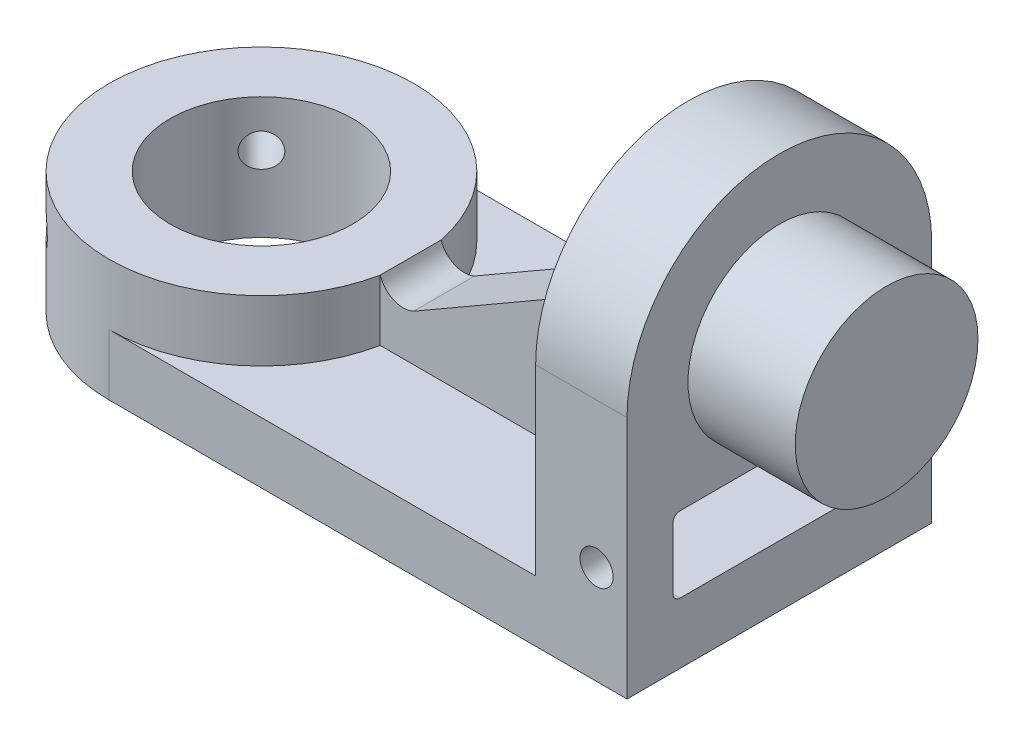
SolidWorks part; units mm, degrees
material "Alloy Steel"
ref_plane "Front Plane" through (0, 0, 0) normal (0, 0, 1) x (1, 0, 0)
ref_plane "Top Plane" through (0, 0, 0) normal (0, 1, 0) x (1, 0, 0)
ref_plane "Right Plane" through (0, 0, 0) normal (1, 0, 0) x (0, 0, -1)
sketch "Sketch4" plane through (0, 0, 0) normal (0, 1, 0) x (1, 0, 0)
  line L1 (-15.9224, 13.1738) -> (38.0526, 13.1738)
  line L2 (-15.9224, 13.1738) -> (-15.9224, -18.5762)
  line L3 (-15.9224, -18.5762) -> (38.0526, -18.5762)
  line L4 (38.0526, 13.1738) -> (38.0526, -18.5762)
  arc A0 (-15.9224, 13.1738) -> (-15.9224, -18.5762) centre (-15.9224, -2.7012) ccw
  dimension "D1" = 53.975
  dimension "D2" = 31.75
extrude "Boss-Extrude1" add sketch "Sketch4" along normal blind 6.35 contours L2 A0 | L4 L1 L2 L3
sketch "Sketch5" plane through (0, 6.35, 0) normal (0, 1, 0) x (1, 0, 0)
  circle A0 centre (-15.9224, -2.7012) radius 15.875
  arc A1 (-15.9224, 13.1738) -> (-15.9224, -18.5762) centre (-15.9224, -2.7012) ccw construction
  dimension "D1" = 31.75
extrude "Boss-Extrude2" add sketch "Sketch5" along normal blind 6.35
sketch "Sketch6" plane through (0, 12.7, 0) normal (0, 1, 0) x (1, 0, 0)
  circle A0 centre (-15.9224, -2.7012) radius 9.525
  circle A1 centre (-15.9224, -2.7012) radius 15.875 construction
  dimension "D1" = 19.05
extrude "Cut-Extrude1" cut sketch "Sketch6" against normal through all both and the other way through all
sketch "Sketch7" plane through (0, 0, 18.5762) normal (0, 0, 1) x (1, 0, 0)
  line L0 (-0.0474, 12.7) -> (-31.7974, 12.7) construction
  line L1 (38.0526, 0) -> (28.5276, 0)
  line L2 (38.0526, 0) -> (38.0526, 25.4)
  line L3 (38.0526, 25.4) -> (28.5276, 25.4)
  line L4 (28.5276, 0) -> (28.5276, 25.4)
  dimension "D1" = 9.525
  dimension "D2" = 12.7
extrude "Boss-Extrude3" add sketch "Sketch7" against normal up to surface (31.75 mm away) up to face at (11.0651, 3.175, -13.1738)
sketch "Sketch8" plane through (38.0526, 0, 0) normal (1, 0, 0) x (0, 0, -1)
  line L0 (13.1738, 25.4) -> (-18.5762, 25.4) construction
  line L1 (-18.5762, 25.4) -> (13.1738, 25.4)
  arc A0 (-18.5762, 25.4) -> (13.1738, 25.4) centre (-2.7012, 25.4) cw
extrude "Boss-Extrude4" add sketch "Sketch8" against normal up to surface (9.525 mm away) up to face at (28.5276, 15.875, 2.7012)
sketch "Sketch9" plane through (38.0526, 0, 0) normal (1, 0, 0) x (0, 0, -1)
  circle A0 centre (-2.7012, 25.4) radius 9.525
  arc A1 (13.1738, 25.4) -> (-18.5762, 25.4) centre (-2.7012, 25.4) ccw construction
  dimension "D1" = 19.05
extrude "Boss-Extrude5" add sketch "Sketch9" along normal blind 11.176
sketch "Sketch10" plane through (38.0526, 0, 0) normal (1, 0, 0) x (0, 0, -1)
  line L0 (-18.5762, 25.4) -> (-18.5762, 0) construction
  line L1 (-13.039, 14.224) -> (7.662, 14.224)
  line L2 (-13.801, 13.462) -> (-13.801, 7.112)
  line L3 (-13.039, 6.35) -> (7.662, 6.35)
  line L4 (8.424, 13.462) -> (8.424, 7.112)
  line L5 (13.1738, 6.35) -> (-18.5762, 6.35) construction
  arc A0 (8.424, 7.112) -> (7.662, 6.35) centre (7.662, 7.112) cw
  arc A1 (-13.801, 7.112) -> (-13.039, 6.35) centre (-13.039, 7.112) ccw
  arc A2 (-13.801, 13.462) -> (-13.039, 14.224) centre (-13.039, 13.462) cw
  arc A3 (7.662, 14.224) -> (8.424, 13.462) centre (7.662, 13.462) cw
  point P10 (8.424, 6.35)
  point P13 (-13.801, 6.35)
  point P18 (8.424, 14.224)
  dimension "D4" = 0.762
  dimension "D1" = 7.874
  dimension "D2" = 22.225
  dimension "D3" = 4.7752
extrude "Cut-Extrude2" cut sketch "Sketch10" against normal blind 8.001 contours L2 A1 L3 A0 L4 A3 L1 A2
sketch "Sketch11" plane through (0, 6.35, 0) normal (0, 1, 0) x (1, 0, 0)
  arc A0 (-15.9224, -18.5762) -> (-15.9224, 13.1738) centre (-15.9224, -2.7012) ccw construction
  point P0 (-0.0474, -2.7012)
ref_plane "Plane1" through (0, 0, 2.7012) normal (0, 0, 1) x (1, 0, 0)
sketch "Sketch12" plane through (0, 0, 2.7012) normal (0, 0, 1) x (1, 0, 0)
  line L0 (28.5276, 25.855) -> (3.1028, 11.176)
  line L1 (28.5276, 41.275) -> (28.5276, 25.4) construction
  line L2 (-0.0474, 6.35) -> (-0.0474, 12.7) construction
  line L3 (-0.0474, 12.7) -> (-0.0474, 6.35)
  line L4 (-0.0474, 6.35) -> (28.5276, 6.35)
  line L5 (28.5276, 6.35) -> (28.5276, 25.855)
  line L6 (3.1028, 11.176) -> (3.1028, 6.35)
  arc A0 (3.1028, 11.176) -> (-0.0474, 12.7) centre (2.3295, 13.5954) cw
  dimension "D1" = 2.54
  dimension "D3" = 30
extrude "Boss-Extrude11" add sketch "Sketch12" along normal blind 3.175 and the other way blind 3.175 contours L0 L6 L4 L5
sketch "Sketch17" plane through (0, 12.7, 0) normal (0, 1, 0) x (1, 0, 0)
  line L0 (3.1028, 0.4738) -> (-0.3682, 0.4738)
  line L1 (3.1028, -5.8762) -> (-0.3682, -5.8762)
  line L2 (3.1028, 0.4738) -> (3.1028, -5.8762)
  circle A1 centre (-15.9224, -2.7012) radius 15.875
  arc A2 (-0.3682, -5.8762) -> (-0.3682, 0.4738) centre (-15.9224, -2.7012) ccw
  dimension "D1" = 0
extrude "Boss-Extrude12" add sketch "Sketch17" against normal up to surface (6.35 mm away)
sketch "Sketch19" plane through (0, 0, -0.4738) normal (0, 0, -1) x (-1, 0, 0)
  line L0 (0.3682, 12.7) -> (-3.1028, 12.7)
  line L1 (-3.1028, 12.7) -> (-3.1028, 11.176)
  arc A0 (-3.1028, 11.176) -> (0.3682, 12.7) centre (-2.0471, 13.4862) ccw
  dimension "D1" = 2.54
extrude "Cut-Extrude3" cut sketch "Sketch19" against normal through all and the other way through all
sketch "Sketch20" plane through (0, 12.7, 0) normal (0, 1, 0) x (1, 0, 0)
  line L0 (-15.9224, -2.7012) -> (-47.5979, -2.7012) construction
  line L1 (-15.9224, -2.7012) -> (-38.3731, -25.1518) construction
  arc A0 (-0.3682, 0.4738) -> (-0.3682, -5.8762) centre (-15.9224, -2.7012) ccw construction
  point P7 (0, 0)
  point P8 (0, 0)
  point P9 (0, 0)
  point P10 (-27.1477, -13.9265)
  point P11 (0, 0)
  dimension "D1" = 45
ref_plane "Plane2" through (-27.1477, 12.7, 13.9265) normal (-0.7071, 0, 0.7071) x (0.7071, 0, 0.7071)
sketch "Sketch21" plane through (-27.1477, 12.7, 13.9265) normal (-0.7071, 0, 0.7071) x (0.7071, 0, 0.7071)
  circle A0 centre (0, -4.826) radius 1.7272
  point P2 (0, 0)
  dimension "D1" = 3.4544
  dimension "D2" = 4.826
extrude "Cut-Extrude5" cut sketch "Sketch21" against normal up to next
pattern_circular "CirPattern1" count 2 every 90 of "Cut-Extrude5"
fillet "Fillet3" radius 0.762 2 edges at (28.5276, 16.1025, -0.4738) (28.5276, 16.1025, 5.8762)
sketch "Sketch22" plane through (0, 0, 18.5762) normal (0, 0, 1) x (1, 0, 0)
  line L0 (38.0526, 25.4) -> (38.0526, 0) construction
  line L1 (-15.9224, 0) -> (38.0526, 0) construction
  circle A0 centre (34.8776, 10.287) radius 1.7272
  dimension "D1" = 3.4544
  dimension "D2" = 3.175
  dimension "D3" = 10.287
extrude "Cut-Extrude6" cut sketch "Sketch22" against normal through all and the other way through all
equation "\"A\"= 2.125in"
equation "\"B\"= 1.25in"
equation "\"D1@Sketch4\"=\"A\""
